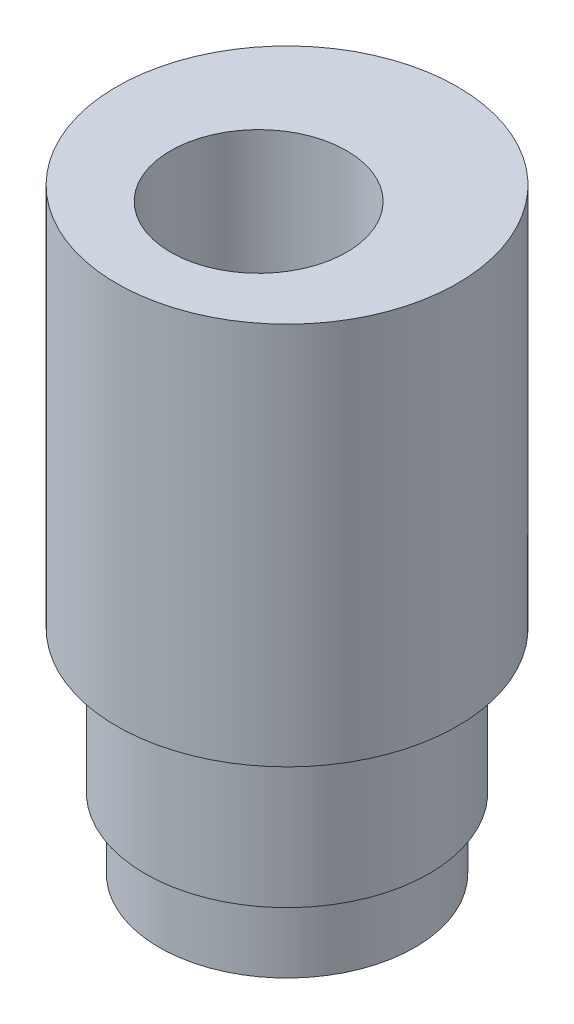
SolidWorks part; units mm, degrees
ref_plane "Front Plane" through (0, 0, 0) normal (0, 0, 1) x (1, 0, 0)
ref_plane "Top Plane" through (0, 0, 0) normal (0, 1, 0) x (1, 0, 0)
ref_plane "Right Plane" through (0, 0, 0) normal (1, 0, 0) x (0, 0, -1)
ref_axis "Axis1" through (0, -43.5149, 0) along (0, 1, 0)
sketch "Sketch4" plane through (0, 0, 0) normal (1, 0, 0) x (0, 0, -1)
  line L7 (-4.5, 2.5) -> (-5, 2.5)
  line L8 (-5, 2.5) -> (-5, 7.5)
  line L10 (0, 44.2539) -> (0, -44.2539) construction
  line L15 (-4.5, 2.5) -> (-4.5, 0)
  line L20 (-5, 7.5) -> (-6, 7.5)
  line L21 (-6, 7.5) -> (-6, 21)
  line L22 (-6, 21) -> (0, 21)
  line L23 (0, 21) -> (0, 0)
  line L24 (0, 0) -> (-4.5, 0)
  dimension "D1" = 13.5
  dimension "D2" = 5
  dimension "D3" = 0.5
  dimension "D4" = 2.5
  dimension "D5" = 1
  dimension "D6" = 5
revolve "Revolve1" add sketch "Sketch4" angle 360 about axis through (0, -43.5149, 0) along (0, 1, 0)
sketch "Sketch5" plane through (0, 0, 0) normal (0, -1, 0) x (1, 0, 0)
  line L0 (0, -44.7868) -> (0, 44.7868) construction
  line L1 (44.2539, 0) -> (-44.2539, 0) construction
  circle A0 centre (0, 1) radius 3.1
  dimension "D1" = 6.2
  dimension "D2" = 1
extrude "Cut-Extrude1" cut sketch "Sketch5" against normal through all
